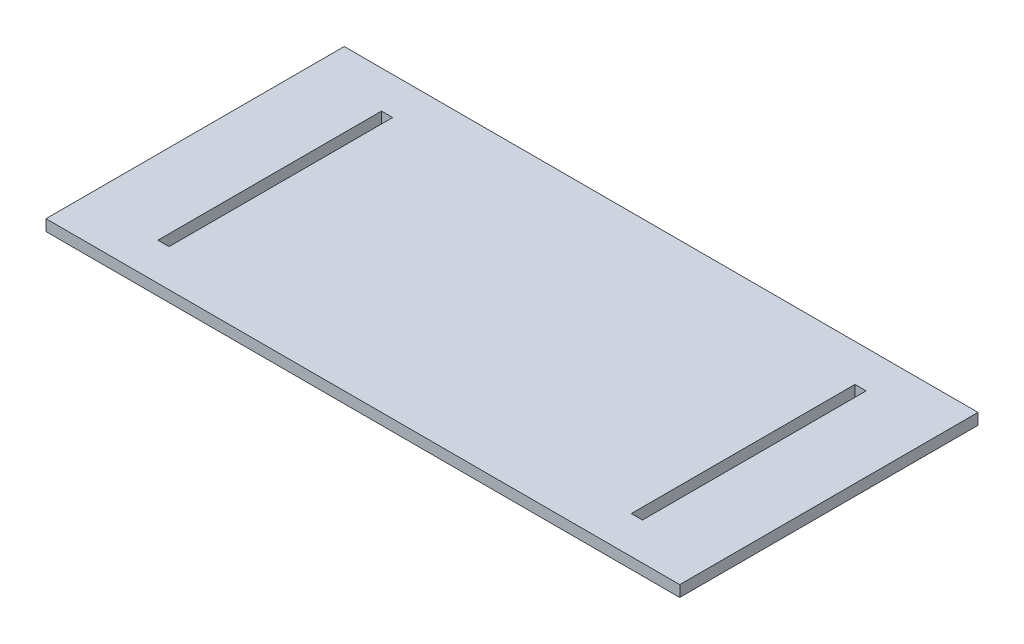
SolidWorks part; units mm, degrees
ref_plane "Front Plane" through (0, 0, 0) normal (0, 0, 1) x (1, 0, 0)
ref_plane "Top Plane" through (0, 0, 0) normal (0, 1, 0) x (1, 0, 0)
ref_plane "Right Plane" through (0, 0, 0) normal (1, 0, 0) x (0, 0, -1)
sketch "Sketch1" plane through (0, 0, 0) normal (0, 1, 0) x (1, 0, 0)
  line L1 (0, 0) -> (170, 0)
  line L2 (0, 0) -> (0, 80)
  line L3 (0, 80) -> (170, 80)
  line L4 (170, 0) -> (170, 80)
  dimension "D1" = 170
  dimension "D2" = 80
extrude "Boss-Extrude1" add sketch "Sketch1" along normal blind 3
sketch "Sketch2" plane through (0, 0, 0) normal (0, 1, 0) x (1, 0, 0)
  line L0 (85, 80) -> (85, 0)
  line L1 (20, 70) -> (23, 70)
  line L2 (20, 70) -> (20, 10)
  line L3 (20, 10) -> (23, 10)
  line L4 (23, 70) -> (23, 10)
  line L5 (170, 80) -> (0, 80) construction
  line L6 (0, 0) -> (170, 0) construction
  line L7 (150, 10) -> (147, 10)
  line L8 (150, 70) -> (147, 70)
  line L9 (150, 70) -> (150, 10)
  line L10 (147, 70) -> (147, 10)
  dimension "D1" = 20
  dimension "D2" = 3
  dimension "D3" = 10
  dimension "D4" = 10
extrude "Cut-Extrude1" cut sketch "Sketch2" along normal blind 10 contours L4 L1 L2 L3 | L8 L10 L7 L9
sketch "Sketch3" plane through (0, 0, 0) normal (0, 1, 0) x (1, 0, 0)
  line L0 (20, 28.65) -> (20, 51.35)
  line L1 (20, 70) -> (20, 10) construction
  line L2 (20, 51.35) -> (1.5, 51.35)
  line L3 (1.5, 51.35) -> (1.5, 28.65)
  line L4 (1.5, 40) -> (20, 40)
  line L5 (20, 40) -> (20, 47.5)
  line L6 (20, 28.65) -> (1.5, 28.65)
  line L7 (85, 80) -> (85, 0)
  line L8 (170, 80) -> (0, 80) construction
  line L9 (0, 0) -> (170, 0) construction
  line L10 (168.5, 40) -> (150, 40)
  line L11 (150, 28.65) -> (150, 51.35)
  line L12 (150, 51.35) -> (168.5, 51.35)
  line L13 (168.5, 51.35) -> (168.5, 28.65)
  line L14 (150, 28.65) -> (168.5, 28.65)
  circle A0 centre (10.4576, 40) radius 12.137
  circle A1 centre (159.5424, 40) radius 12.137
  dimension "D1" = 11.35
  dimension "D2" = 18.5
  dimension "D3" = 7.5
extrude "Cut-Extrude2" [suppressed] cut sketch "Sketch3" along normal blind 10 contours L0 A0 L2 L3 L4 | L6 A0 L0 L4 L3 | L2 A0 | L6 A0 | A1 L14 L13 L10 L11 | A1 L11 L10 L13 L12 | A1 L12 | A1 L14
